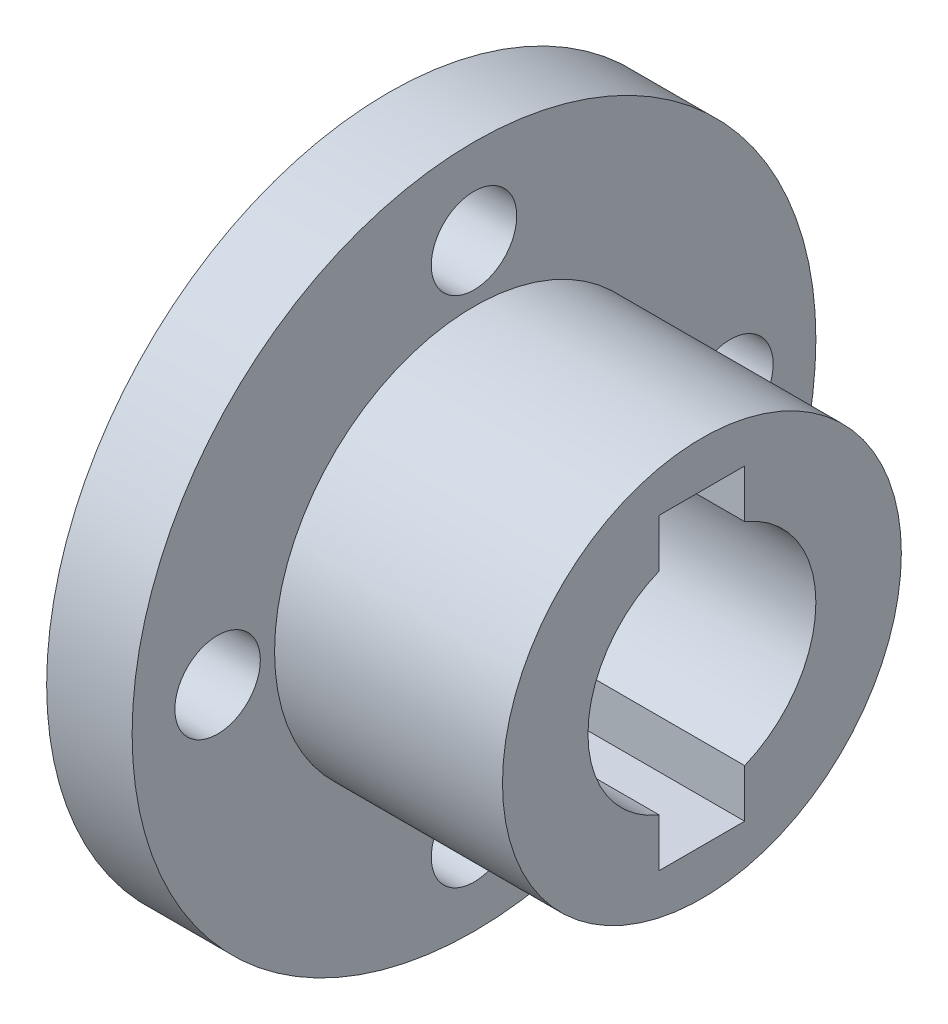
SolidWorks part; units mm, degrees
ref_plane "前视基准面" through (0, 0, 0) normal (0, 0, 1) x (1, 0, 0)
ref_plane "上视基准面" through (0, 0, 0) normal (0, 1, 0) x (1, 0, 0)
ref_plane "右视基准面" through (0, 0, 0) normal (1, 0, 0) x (0, 0, -1)
other "Configuration Table"
sketch "草图1" plane through (0, 0, 0) normal (0, 1, 0) x (1, 0, 0)
  line L0 (0, 0) -> (0, 12)
  line L1 (0, 12) -> (3, 12)
  line L2 (3, 12) -> (3, 7)
  line L3 (3, 7) -> (11, 7)
  line L4 (11, 7) -> (11, 4)
  line L5 (3, 0) -> (0, 0)
  line L6 (3, 0) -> (3, 4)
  line L7 (3, 4) -> (11, 4)
  dimension "D1" = 4
  dimension "D2" = 3
  dimension "D3" = 5
  dimension "D4" = 8
  dimension "D5" = 3
revolve "旋转1" add sketch "草图1" angle 360 about L5
sketch "草图2" plane through (11, 0, 0) normal (1, 0, 0) x (0, 0, -1)
  line L0 (0, 0) -> (16.5026, 0) construction
  line L1 (1.5, -5.4) -> (1.5, -3.7081)
  line L2 (-1.5, 5.4) -> (1.5, 5.4)
  line L3 (1.5, 5.4) -> (1.5, 3.7081)
  line L4 (-1.5, 5.4) -> (-1.5, 3.7081)
  line L5 (-1.5, -5.4) -> (1.5, -5.4)
  line L6 (-1.5, -5.4) -> (-1.5, -3.7081)
  arc A0 (1.5, -3.7081) -> (-1.5, -3.7081) centre (0, 0) cw
  circle A1 centre (0, 0) radius 4 construction
  arc A2 (1.5, 3.7081) -> (-1.5, 3.7081) centre (0, 0) ccw
extrude "切除-拉伸1" cut sketch "草图2" against normal through all
sketch "草图3" plane through (3, 0, 0) normal (1, 0, 0) x (0, 0, -1)
  line L0 (0, 0) -> (0, -12.8678) construction
  circle A0 centre (0, 0) radius 9 construction
  circle A1 centre (0, 9) radius 1.5
  circle A2 centre (9, 0) radius 1.5
  circle A3 centre (0, -9) radius 1.5
  circle A4 centre (-9, 0) radius 1.5
  point P15 (0, 0)
  dimension "D1" = 18
  dimension "D2" = 3
  dimension "D3" = 4
extrude "切除-拉伸2" cut sketch "草图3" against normal up to next
sketch "草图5" plane through (0, 0, 0) normal (-1, 0, 0) x (0, 0, 1)
  circle A0 centre (0, 0) radius 1.7
  dimension "D1" = 3.4
extrude "切除-拉伸3" cut sketch "草图5" against normal through all
sketch "草图6" plane through (3, 0, 0) normal (1, 0, 0) x (0, 0, -1)
  circle A0 centre (0, 0) radius 4
extrude "切除-拉伸4" cut sketch "草图6" against normal through all
